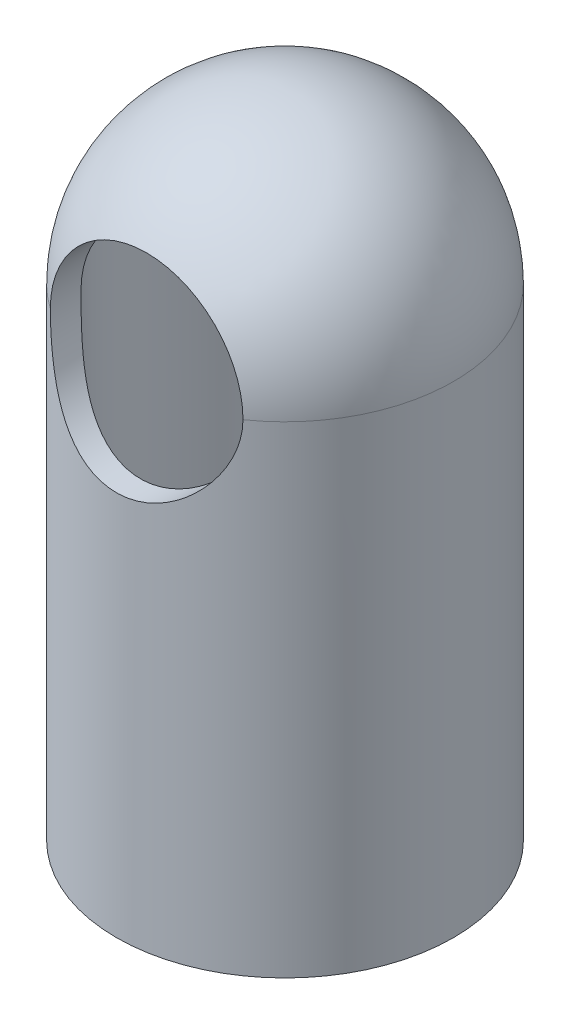
SolidWorks part; units mm, degrees
material "6061 合金"
ref_plane "前视基准面" through (0, 0, 0) normal (0, 0, 1) x (1, 0, 0)
ref_plane "上视基准面" through (0, 0, 0) normal (0, 1, 0) x (1, 0, 0)
ref_plane "右视基准面" through (0, 0, 0) normal (1, 0, 0) x (0, 0, -1)
sketch "草图1" plane through (0, 0, 0) normal (0, 1, 0) x (1, 0, 0)
  circle A0 centre (0, 0) radius 6
  circle A1 centre (0, 0) radius 7
  dimension "D1" = 12
  dimension "D2" = 1
extrude "凸台-拉伸1" add sketch "草图1" along normal blind 20
sketch "草图2" plane through (0, 0, 0) normal (0, 0, 1) x (1, 0, 0)
  line L0 (6, 20) -> (-6, 20) construction
  line L1 (-7, 20) -> (-6, 20)
  line L2 (0, 20) -> (0, 27) construction
  line L3 (0, 27) -> (0, 26)
  arc A0 (0, 27) -> (-7, 20) centre (0, 20) ccw
  arc A1 (0, 26) -> (-6, 20) centre (0, 20) ccw
revolve "旋转1" add sketch "草图2" angle 360 about L2
sketch "草图3" plane through (0, 0, 0) normal (0, 0, 1) x (1, 0, 0)
  line L0 (7, 20) -> (-7, 20) construction
  circle A0 centre (0, 20) radius 4
  dimension "D1" = 8
extrude "切除-拉伸1" cut sketch "草图3" against normal through all both and the other way through all
